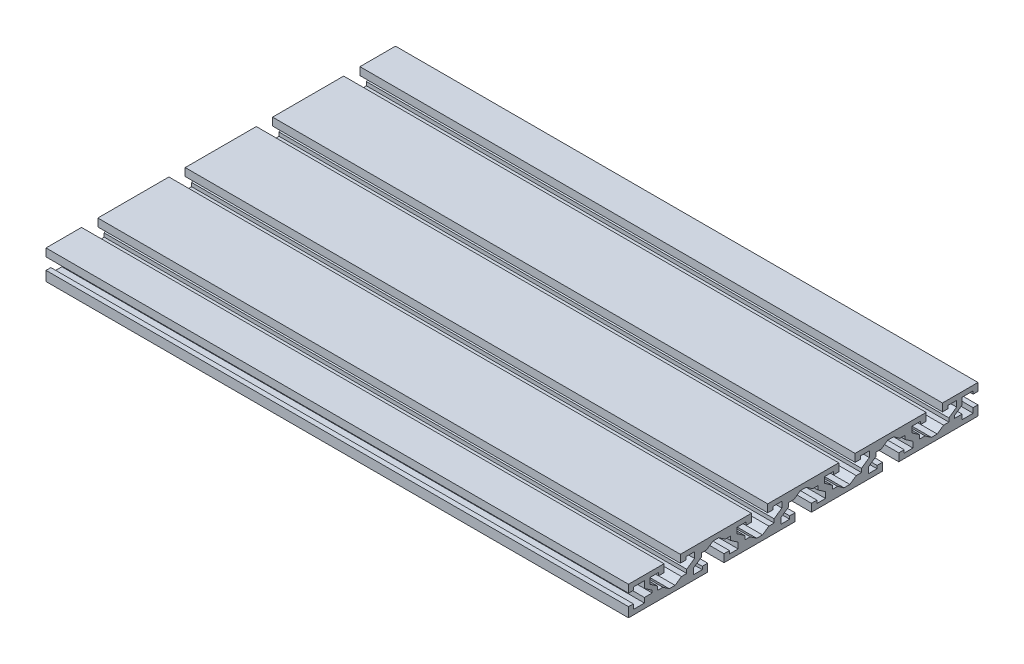
SolidWorks part; units mm, degrees
material "1060 Сплав"
ref_plane "Спереди" through (0, 0, 0) normal (0, 0, 1) x (1, 0, 0)
ref_plane "Сверху" through (0, 0, 0) normal (0, 1, 0) x (1, 0, 0)
ref_plane "Справа" through (0, 0, 0) normal (1, 0, 0) x (0, 0, -1)
other "Configuration Table"
sketch "Эскиз1" plane through (0, 0, 0) normal (0, 1, 0) x (1, 0, 0)
  line L1 (-150, -90) -> (150, -90)
  line L2 (-150, -90) -> (-150, 90)
  line L3 (-150, 90) -> (150, 90)
  line L4 (150, -90) -> (150, 90)
  line L5 (-150, -90) -> (150, 90) construction
  line L6 (-150, 90) -> (150, -90) construction
  point P0 (0, 0)
  dimension "D1" = 300
  dimension "D2" = 180
extrude "Бобышка-Вытянуть1" add sketch "Эскиз1" along normal blind 15
sketch "Эскиз3" plane through (0, 0, 0) normal (1, 0, 0) x (0, 0, -1)
  line L0 (0, -1000) -> (0, 49000) construction
  line L1 (4.2, 0) -> (4.2, 4)
  line L2 (-4.2, 0) -> (-4.2, 4)
  line L3 (-4.2, 4) -> (-7, 4)
  line L4 (-90, 0) -> (90, 0)
  line L5 (-90, 15) -> (-90, 0)
  line L6 (90, 15) -> (-90, 15)
  line L7 (90, 0) -> (90, 15)
  line L8 (-90, 0) -> (90, 0)
  line L9 (-90, 15) -> (-90, 0)
  line L10 (90, 15) -> (-90, 15)
  line L11 (90, 0) -> (90, 15)
  line L12 (-7, 4) -> (-7, 2.5)
  line L13 (-7, 2.5) -> (-11.5, 2.5)
  line L14 (-11.5, 2.5) -> (-11.5, 5.5)
  line L15 (-11.5, 5.5) -> (-7.5, 8.3)
  line L16 (-7.5, 8.3) -> (-7.5, 10.2)
  line L17 (-7.5, 10.2) -> (-4.7857, 10.2)
  line L18 (-4.7857, 10.2) -> (-1.5, 12.5)
  line L19 (-1.5, 12.5) -> (1.5, 12.5)
  line L20 (-7.5, 8.3) -> (-4.7857, 10.2) construction
  line L21 (4.7857, 10.2) -> (1.5, 12.5)
  line L22 (4.2, 4) -> (7, 4)
  line L23 (7.5, 10.2) -> (4.7857, 10.2)
  line L24 (7.5, 8.3) -> (7.5, 10.2)
  line L25 (11.5, 5.5) -> (7.5, 8.3)
  line L26 (11.5, 2.5) -> (11.5, 5.5)
  line L27 (7, 2.5) -> (11.5, 2.5)
  line L28 (7, 4) -> (7, 2.5)
  line L29 (49.2, 0) -> (49.2, 4)
  line L30 (40.8, 0) -> (40.8, 4)
  line L31 (40.8, 4) -> (38, 4)
  line L32 (38, 4) -> (38, 2.5)
  line L33 (38, 2.5) -> (33.5, 2.5)
  line L34 (33.5, 2.5) -> (33.5, 5.5)
  line L35 (33.5, 5.5) -> (37.5, 8.3)
  line L36 (37.5, 8.3) -> (37.5, 10.2)
  line L37 (37.5, 10.2) -> (40.2143, 10.2)
  line L38 (40.2143, 10.2) -> (43.5, 12.5)
  line L39 (43.5, 12.5) -> (46.5, 12.5)
  line L40 (49.7857, 10.2) -> (46.5, 12.5)
  line L41 (49.2, 4) -> (52, 4)
  line L42 (52.5, 10.2) -> (49.7857, 10.2)
  line L43 (52.5, 8.3) -> (52.5, 10.2)
  line L44 (56.5, 5.5) -> (52.5, 8.3)
  line L45 (56.5, 2.5) -> (56.5, 5.5)
  line L46 (52, 2.5) -> (56.5, 2.5)
  line L47 (52, 4) -> (52, 2.5)
  line L48 (37.5, 8.3) -> (40.2143, 10.2) construction
  line L49 (-40.8, 0) -> (-40.8, 4)
  line L50 (-49.2, 0) -> (-49.2, 4)
  line L51 (-49.2, 4) -> (-52, 4)
  line L52 (-52, 4) -> (-52, 2.5)
  line L53 (-52, 2.5) -> (-56.5, 2.5)
  line L54 (-56.5, 2.5) -> (-56.5, 5.5)
  line L55 (-56.5, 5.5) -> (-52.5, 8.3)
  line L56 (-52.5, 8.3) -> (-52.5, 10.2)
  line L57 (-52.5, 10.2) -> (-49.7857, 10.2)
  line L58 (-49.7857, 10.2) -> (-46.5, 12.5)
  line L59 (-46.5, 12.5) -> (-43.5, 12.5)
  line L60 (-40.2143, 10.2) -> (-43.5, 12.5)
  line L61 (-40.8, 4) -> (-38, 4)
  line L62 (-37.5, 10.2) -> (-40.2143, 10.2)
  line L63 (-37.5, 8.3) -> (-37.5, 10.2)
  line L64 (-33.5, 5.5) -> (-37.5, 8.3)
  line L65 (-33.5, 2.5) -> (-33.5, 5.5)
  line L66 (-38, 2.5) -> (-33.5, 2.5)
  line L67 (-38, 4) -> (-38, 2.5)
  line L68 (-52.5, 8.3) -> (-49.7857, 10.2) construction
  point P7 (0, 0)
  point P11 (4.2, 2)
  point P23 (0, 12.5)
  point P46 (45, 12.5)
  point P67 (-45, 12.5)
  dimension "D2" = 8.4
  dimension "D3" = 4
  dimension "D4" = 2.8
  dimension "D5" = 2.5
  dimension "D6" = 23
  dimension "D7" = 2.5
  dimension "D8" = 3
  dimension "D9" = 15
  dimension "D10" = 4.8
  dimension "D11" = 3
  dimension "D12" = 2
  dimension "D13" = 45
  dimension "D14" = 2
  dimension "D15" = 45
  dimension "D1" = 0
extrude "Вырез-Вытянуть1" cut sketch "Эскиз3" against normal through all both and the other way through all contours L61 L67 L66 L65 L64 L63 L62 L60 L59 L58 L57 L56 L55 L54 L53 L52 L51 L50 L8 L49 | L22 L28 L27 L26 L25 L24 L23 L21 L19 L18 L17 L16 L15 L14 L13 L12 L3 L2 L8 L1 | L41 L47 L46 L45 L44 L43 L42 L40 L39 L38 L37 L36 L35 L34 L33 L32 L31 L30 L8 L29
sketch "Эскиз4" plane through (0, 0, 0) normal (1, 0, 0) x (0, 0, -1)
  line L18 (-71.7, 11) -> (-71.7, 15)
  line L19 (-71.7, 15) -> (-63.3, 15) construction
  line L20 (0, -1000) -> (0, 49000) construction
  line L21 (-71.7, 11) -> (-74.5, 11)
  line L22 (-74.5, 11) -> (-74.5, 12.5)
  line L23 (-74.5, 12.5) -> (-79, 12.5)
  line L24 (-79, 12.5) -> (-79, 9.5)
  line L25 (-79, 9.5) -> (-75, 6.7)
  line L26 (-75, 6.7) -> (-75, 4.8)
  line L27 (-75, 4.8) -> (-72.2857, 4.8)
  line L28 (-72.2857, 4.8) -> (-69, 2.5)
  line L29 (-69, 2.5) -> (-66, 2.5)
  line L30 (-66, 2.5) -> (-62.7143, 4.8)
  line L31 (-62.7143, 4.8) -> (-60, 4.8)
  line L32 (-60, 4.8) -> (-60, 6.7)
  line L33 (-60, 6.7) -> (-56, 9.5)
  line L34 (-56, 9.5) -> (-56, 12.5)
  line L35 (-56, 12.5) -> (-60.5, 12.5)
  line L36 (-60.5, 12.5) -> (-60.5, 11)
  line L37 (-60.5, 11) -> (-63.3, 11)
  line L38 (-63.3, 11) -> (-63.3, 15)
  line L39 (-67.5, 2.5) -> (-67.5, 15) construction
  line L40 (-26.7, 11) -> (-29.5, 11)
  line L41 (-29.5, 11) -> (-29.5, 12.5)
  line L42 (-29.5, 12.5) -> (-34, 12.5)
  line L43 (-34, 12.5) -> (-34, 9.5)
  line L44 (-34, 9.5) -> (-30, 6.7)
  line L45 (-30, 6.7) -> (-30, 4.8)
  line L46 (-30, 4.8) -> (-27.2857, 4.8)
  line L47 (-27.2857, 4.8) -> (-24, 2.5)
  line L48 (-24, 2.5) -> (-21, 2.5)
  line L49 (-21, 2.5) -> (-17.7143, 4.8)
  line L50 (-17.7143, 4.8) -> (-15, 4.8)
  line L51 (-15, 4.8) -> (-15, 6.7)
  line L52 (-15, 6.7) -> (-11, 9.5)
  line L53 (-11, 9.5) -> (-11, 12.5)
  line L54 (-11, 12.5) -> (-15.5, 12.5)
  line L55 (-15.5, 12.5) -> (-15.5, 11)
  line L56 (-15.5, 11) -> (-18.3, 11)
  line L57 (-26.7, 11) -> (-26.7, 15)
  line L58 (-18.3, 11) -> (-18.3, 15)
  line L59 (18.3, 11) -> (15.5, 11)
  line L60 (15.5, 11) -> (15.5, 12.5)
  line L61 (15.5, 12.5) -> (11, 12.5)
  line L62 (11, 12.5) -> (11, 9.5)
  line L63 (11, 9.5) -> (15, 6.7)
  line L64 (-40.8, 0) -> (-4.2, 0)
  line L65 (-40.8, 4) -> (-40.8, 0)
  line L66 (-38, 4) -> (-40.8, 4)
  line L67 (-38, 2.5) -> (-38, 4)
  line L68 (-33.5, 2.5) -> (-38, 2.5)
  line L69 (-33.5, 5.5) -> (-33.5, 2.5)
  line L70 (-37.5, 8.3) -> (-33.5, 5.5)
  line L71 (-37.5, 10.2) -> (-37.5, 8.3)
  line L72 (-40.2143, 10.2) -> (-37.5, 10.2)
  line L73 (-43.5, 12.5) -> (-40.2143, 10.2)
  line L74 (-46.5, 12.5) -> (-43.5, 12.5)
  line L75 (-49.7857, 10.2) -> (-46.5, 12.5)
  line L76 (-52.5, 10.2) -> (-49.7857, 10.2)
  line L77 (-52.5, 8.3) -> (-52.5, 10.2)
  line L78 (-56.5, 5.5) -> (-52.5, 8.3)
  line L79 (-56.5, 2.5) -> (-56.5, 5.5)
  line L80 (-52, 2.5) -> (-56.5, 2.5)
  line L81 (-52, 4) -> (-52, 2.5)
  line L82 (-49.2, 4) -> (-52, 4)
  line L83 (-49.2, 0) -> (-49.2, 4)
  line L84 (-90, 0) -> (-49.2, 0)
  line L85 (-90, 15) -> (-90, 0)
  line L86 (90, 15) -> (-90, 15)
  line L87 (90, 0) -> (90, 15)
  line L88 (49.2, 0) -> (90, 0)
  line L89 (49.2, 4) -> (49.2, 0)
  line L90 (52, 4) -> (49.2, 4)
  line L91 (52, 2.5) -> (52, 4)
  line L92 (56.5, 2.5) -> (52, 2.5)
  line L93 (56.5, 5.5) -> (56.5, 2.5)
  line L94 (52.5, 8.3) -> (56.5, 5.5)
  line L95 (52.5, 10.2) -> (52.5, 8.3)
  line L96 (49.7857, 10.2) -> (52.5, 10.2)
  line L97 (46.5, 12.5) -> (49.7857, 10.2)
  line L98 (43.5, 12.5) -> (46.5, 12.5)
  line L99 (40.2143, 10.2) -> (43.5, 12.5)
  line L100 (37.5, 10.2) -> (40.2143, 10.2)
  line L101 (37.5, 8.3) -> (37.5, 10.2)
  line L102 (33.5, 5.5) -> (37.5, 8.3)
  line L103 (33.5, 2.5) -> (33.5, 5.5)
  line L104 (38, 2.5) -> (33.5, 2.5)
  line L105 (38, 4) -> (38, 2.5)
  line L106 (40.8, 4) -> (38, 4)
  line L107 (40.8, 0) -> (40.8, 4)
  line L108 (4.2, 0) -> (40.8, 0)
  line L109 (4.2, 4) -> (4.2, 0)
  line L110 (7, 4) -> (4.2, 4)
  line L111 (7, 2.5) -> (7, 4)
  line L112 (11.5, 2.5) -> (7, 2.5)
  line L113 (11.5, 5.5) -> (11.5, 2.5)
  line L114 (7.5, 8.3) -> (11.5, 5.5)
  line L115 (7.5, 10.2) -> (7.5, 8.3)
  line L116 (4.7857, 10.2) -> (7.5, 10.2)
  line L117 (1.5, 12.5) -> (4.7857, 10.2)
  line L118 (-1.5, 12.5) -> (1.5, 12.5)
  line L119 (-4.7857, 10.2) -> (-1.5, 12.5)
  line L120 (-7.5, 10.2) -> (-4.7857, 10.2)
  line L121 (-7.5, 8.3) -> (-7.5, 10.2)
  line L122 (-11.5, 5.5) -> (-7.5, 8.3)
  line L123 (-11.5, 2.5) -> (-11.5, 5.5)
  line L124 (-7, 2.5) -> (-11.5, 2.5)
  line L125 (-7, 4) -> (-7, 2.5)
  line L126 (-4.2, 4) -> (-7, 4)
  line L127 (-4.2, 0) -> (-4.2, 4)
  line L128 (-40.8, 0) -> (-4.2, 0)
  line L129 (-40.8, 4) -> (-40.8, 0)
  line L130 (-38, 4) -> (-40.8, 4)
  line L131 (-38, 2.5) -> (-38, 4)
  line L132 (-33.5, 2.5) -> (-38, 2.5)
  line L133 (-33.5, 5.5) -> (-33.5, 2.5)
  line L134 (-37.5, 8.3) -> (-33.5, 5.5)
  line L135 (-37.5, 10.2) -> (-37.5, 8.3)
  line L136 (-40.2143, 10.2) -> (-37.5, 10.2)
  line L137 (-43.5, 12.5) -> (-40.2143, 10.2)
  line L138 (-46.5, 12.5) -> (-43.5, 12.5)
  line L139 (-49.7857, 10.2) -> (-46.5, 12.5)
  line L140 (-52.5, 10.2) -> (-49.7857, 10.2)
  line L141 (-52.5, 8.3) -> (-52.5, 10.2)
  line L142 (-56.5, 5.5) -> (-52.5, 8.3)
  line L143 (-56.5, 2.5) -> (-56.5, 5.5)
  line L144 (-52, 2.5) -> (-56.5, 2.5)
  line L145 (-52, 4) -> (-52, 2.5)
  line L146 (-49.2, 4) -> (-52, 4)
  line L147 (-49.2, 0) -> (-49.2, 4)
  line L148 (-90, 0) -> (-49.2, 0)
  line L149 (-90, 15) -> (-90, 0)
  line L150 (90, 15) -> (-90, 15)
  line L151 (90, 0) -> (90, 15)
  line L152 (49.2, 0) -> (90, 0)
  line L153 (49.2, 4) -> (49.2, 0)
  line L154 (52, 4) -> (49.2, 4)
  line L155 (52, 2.5) -> (52, 4)
  line L156 (56.5, 2.5) -> (52, 2.5)
  line L157 (56.5, 5.5) -> (56.5, 2.5)
  line L158 (52.5, 8.3) -> (56.5, 5.5)
  line L159 (52.5, 10.2) -> (52.5, 8.3)
  line L160 (49.7857, 10.2) -> (52.5, 10.2)
  line L161 (46.5, 12.5) -> (49.7857, 10.2)
  line L162 (43.5, 12.5) -> (46.5, 12.5)
  line L163 (40.2143, 10.2) -> (43.5, 12.5)
  line L164 (37.5, 10.2) -> (40.2143, 10.2)
  line L165 (37.5, 8.3) -> (37.5, 10.2)
  line L166 (33.5, 5.5) -> (37.5, 8.3)
  line L167 (33.5, 2.5) -> (33.5, 5.5)
  line L168 (38, 2.5) -> (33.5, 2.5)
  line L169 (38, 4) -> (38, 2.5)
  line L170 (40.8, 4) -> (38, 4)
  line L171 (40.8, 0) -> (40.8, 4)
  line L172 (4.2, 0) -> (40.8, 0)
  line L173 (4.2, 4) -> (4.2, 0)
  line L174 (7, 4) -> (4.2, 4)
  line L175 (7, 2.5) -> (7, 4)
  line L176 (11.5, 2.5) -> (7, 2.5)
  line L177 (11.5, 5.5) -> (11.5, 2.5)
  line L178 (7.5, 8.3) -> (11.5, 5.5)
  line L179 (7.5, 10.2) -> (7.5, 8.3)
  line L180 (4.7857, 10.2) -> (7.5, 10.2)
  line L181 (1.5, 12.5) -> (4.7857, 10.2)
  line L182 (-1.5, 12.5) -> (1.5, 12.5)
  line L183 (-4.7857, 10.2) -> (-1.5, 12.5)
  line L184 (-7.5, 10.2) -> (-4.7857, 10.2)
  line L185 (-7.5, 8.3) -> (-7.5, 10.2)
  line L186 (-11.5, 5.5) -> (-7.5, 8.3)
  line L187 (-11.5, 2.5) -> (-11.5, 5.5)
  line L188 (-7, 2.5) -> (-11.5, 2.5)
  line L189 (-7, 4) -> (-7, 2.5)
  line L190 (-4.2, 4) -> (-7, 4)
  line L191 (-4.2, 0) -> (-4.2, 4)
  line L192 (15, 6.7) -> (15, 4.8)
  line L193 (15, 4.8) -> (17.7143, 4.8)
  line L194 (17.7143, 4.8) -> (21, 2.5)
  line L195 (21, 2.5) -> (24, 2.5)
  line L196 (24, 2.5) -> (27.2857, 4.8)
  line L197 (27.2857, 4.8) -> (30, 4.8)
  line L198 (30, 4.8) -> (30, 6.7)
  line L199 (30, 6.7) -> (34, 9.5)
  line L200 (34, 9.5) -> (34, 12.5)
  line L201 (34, 12.5) -> (29.5, 12.5)
  line L202 (29.5, 12.5) -> (29.5, 11)
  line L203 (29.5, 11) -> (26.7, 11)
  line L204 (18.3, 11) -> (18.3, 15)
  line L205 (26.7, 11) -> (26.7, 15)
  line L206 (63.3, 11) -> (60.5, 11)
  line L207 (60.5, 11) -> (60.5, 12.5)
  line L208 (60.5, 12.5) -> (56, 12.5)
  line L209 (56, 12.5) -> (56, 9.5)
  line L210 (56, 9.5) -> (60, 6.7)
  line L211 (60, 6.7) -> (60, 4.8)
  line L212 (60, 4.8) -> (62.7143, 4.8)
  line L213 (62.7143, 4.8) -> (66, 2.5)
  line L214 (66, 2.5) -> (69, 2.5)
  line L215 (69, 2.5) -> (72.2857, 4.8)
  line L216 (72.2857, 4.8) -> (75, 4.8)
  line L217 (75, 4.8) -> (75, 6.7)
  line L218 (75, 6.7) -> (79, 9.5)
  line L219 (79, 9.5) -> (79, 12.5)
  line L220 (79, 12.5) -> (74.5, 12.5)
  line L221 (74.5, 12.5) -> (74.5, 11)
  line L222 (74.5, 11) -> (71.7, 11)
  line L223 (63.3, 11) -> (63.3, 15)
  line L224 (71.7, 11) -> (71.7, 15)
  line L225 (-71.7, 11) -> (-26.7, 11) construction
  dimension "D2" = 8.4
  dimension "D3" = 23
  dimension "D4" = 2.3
  dimension "D5" = 12.5
  dimension "D6" = 4
  dimension "D7" = 3
  dimension "D8" = 14
  dimension "D9" = 3
  dimension "D10" = 1.5
  dimension "D11" = 15
  dimension "D12" = 67.5
  dimension "D14" = 45
  dimension "D1" = 0
  dimension "D13" = 4
extrude "Вырез-Вытянуть2" cut sketch "Эскиз4" against normal through all both and the other way through all contours L38 L150 L18 L21 L22 L23 L24 L25 L26 L27 L28 L29 L30 L31 L32 L33 L34 L35 L36 L37 | L58 L150 L57 L40 L41 L42 L43 L44 L45 L46 L47 L48 L49 L50 L51 L52 L53 L54 L55 L56 | L203 L205 L150 L204 L59 L60 L61 L62 L63 L192 L193 L194 L195 L196 L197 L198 L199 L200 L201 L202 | L222 L224 L150 L223 L206 L207 L208 L209 L210 L211 L212 L213 L214 L215 L216 L217 L218 L219 L220 L221
sketch "Эскиз5" plane through (0, 0, 0) normal (1, 0, 0) x (0, 0, -1)
  line L0 (0, -1000) -> (0, 49000) construction
  line L1 (90, 11) -> (87.5, 11)
  line L2 (87.5, 11) -> (87.5, 12.5)
  line L3 (87.5, 12.5) -> (81.8, 12.5)
  line L4 (81.8, 12.5) -> (81.8, 9.0187)
  line L5 (81.8, 9.0187) -> (77.8, 6.2187)
  line L6 (77.8, 6.2187) -> (77.8, 5)
  line L7 (77.8, 5) -> (81.8, 5)
  line L8 (81.8, 5) -> (81.8, 2.5)
  line L9 (81.8, 2.5) -> (87.5, 2.5)
  line L10 (87.5, 2.5) -> (87.5, 5)
  line L11 (87.5, 5) -> (90, 5)
  line L12 (-87.5, 11) -> (-87.5, 12.5)
  line L13 (-87.5, 12.5) -> (-81.8, 12.5)
  line L14 (-81.8, 12.5) -> (-81.8, 9.0187)
  line L15 (-87.5, 5) -> (-90, 5)
  line L16 (-87.5, 2.5) -> (-87.5, 5)
  line L17 (-81.8, 2.5) -> (-87.5, 2.5)
  line L18 (-81.8, 5) -> (-81.8, 2.5)
  line L19 (-77.8, 5) -> (-81.8, 5)
  line L20 (-77.8, 6.2187) -> (-77.8, 5)
  line L21 (-81.8, 9.0187) -> (-77.8, 6.2187)
  line L22 (-90, 11) -> (-87.5, 11)
  line L144 (-26.7, 15) -> (-63.3, 15)
  line L145 (-63.3, 15) -> (-63.3, 11)
  line L146 (-63.3, 11) -> (-60.5, 11)
  line L147 (-60.5, 11) -> (-60.5, 12.5)
  line L148 (-60.5, 12.5) -> (-56, 12.5)
  line L149 (-56, 12.5) -> (-56, 9.5)
  line L150 (-56, 9.5) -> (-60, 6.7)
  line L151 (-60, 6.7) -> (-60, 4.8)
  line L152 (-60, 4.8) -> (-62.7143, 4.8)
  line L153 (-62.7143, 4.8) -> (-66, 2.5)
  line L154 (-66, 2.5) -> (-69, 2.5)
  line L155 (-69, 2.5) -> (-72.2857, 4.8)
  line L156 (-72.2857, 4.8) -> (-75, 4.8)
  line L157 (-75, 4.8) -> (-75, 6.7)
  line L158 (-75, 6.7) -> (-79, 9.5)
  line L159 (-79, 9.5) -> (-79, 12.5)
  line L160 (-79, 12.5) -> (-74.5, 12.5)
  line L161 (-74.5, 12.5) -> (-74.5, 11)
  line L162 (-74.5, 11) -> (-71.7, 11)
  line L163 (-71.7, 11) -> (-71.7, 15)
  line L164 (-71.7, 15) -> (-90, 15)
  line L165 (-90, 15) -> (-90, 0)
  line L166 (-90, 0) -> (-49.2, 0)
  line L167 (-49.2, 0) -> (-49.2, 4)
  line L168 (-49.2, 4) -> (-52, 4)
  line L169 (-52, 4) -> (-52, 2.5)
  line L170 (-52, 2.5) -> (-56.5, 2.5)
  line L171 (-56.5, 2.5) -> (-56.5, 5.5)
  line L172 (-56.5, 5.5) -> (-52.5, 8.3)
  line L173 (-52.5, 8.3) -> (-52.5, 10.2)
  line L174 (-52.5, 10.2) -> (-49.7857, 10.2)
  line L175 (-49.7857, 10.2) -> (-46.5, 12.5)
  line L176 (-46.5, 12.5) -> (-43.5, 12.5)
  line L177 (-43.5, 12.5) -> (-40.2143, 10.2)
  line L178 (-40.2143, 10.2) -> (-37.5, 10.2)
  line L179 (-37.5, 10.2) -> (-37.5, 8.3)
  line L180 (-37.5, 8.3) -> (-33.5, 5.5)
  line L181 (-33.5, 5.5) -> (-33.5, 2.5)
  line L182 (-33.5, 2.5) -> (-38, 2.5)
  line L183 (-38, 2.5) -> (-38, 4)
  line L184 (-38, 4) -> (-40.8, 4)
  line L185 (-40.8, 4) -> (-40.8, 0)
  line L186 (-40.8, 0) -> (-4.2, 0)
  line L187 (-4.2, 0) -> (-4.2, 4)
  line L188 (-4.2, 4) -> (-7, 4)
  line L189 (-7, 4) -> (-7, 2.5)
  line L190 (-7, 2.5) -> (-11.5, 2.5)
  line L191 (-11.5, 2.5) -> (-11.5, 5.5)
  line L192 (-11.5, 5.5) -> (-7.5, 8.3)
  line L193 (-7.5, 8.3) -> (-7.5, 10.2)
  line L194 (-7.5, 10.2) -> (-4.7857, 10.2)
  line L195 (-4.7857, 10.2) -> (-1.5, 12.5)
  line L196 (-1.5, 12.5) -> (1.5, 12.5)
  line L197 (1.5, 12.5) -> (4.7857, 10.2)
  line L198 (4.7857, 10.2) -> (7.5, 10.2)
  line L199 (7.5, 10.2) -> (7.5, 8.3)
  line L200 (7.5, 8.3) -> (11.5, 5.5)
  line L201 (11.5, 5.5) -> (11.5, 2.5)
  line L202 (11.5, 2.5) -> (7, 2.5)
  line L203 (7, 2.5) -> (7, 4)
  line L204 (7, 4) -> (4.2, 4)
  line L205 (4.2, 4) -> (4.2, 0)
  line L206 (4.2, 0) -> (40.8, 0)
  line L207 (40.8, 0) -> (40.8, 4)
  line L208 (40.8, 4) -> (38, 4)
  line L209 (38, 4) -> (38, 2.5)
  line L210 (38, 2.5) -> (33.5, 2.5)
  line L211 (33.5, 2.5) -> (33.5, 5.5)
  line L212 (33.5, 5.5) -> (37.5, 8.3)
  line L213 (37.5, 8.3) -> (37.5, 10.2)
  line L214 (37.5, 10.2) -> (40.2143, 10.2)
  line L215 (40.2143, 10.2) -> (43.5, 12.5)
  line L216 (43.5, 12.5) -> (46.5, 12.5)
  line L217 (46.5, 12.5) -> (49.7857, 10.2)
  line L218 (49.7857, 10.2) -> (52.5, 10.2)
  line L219 (52.5, 10.2) -> (52.5, 8.3)
  line L220 (52.5, 8.3) -> (56.5, 5.5)
  line L221 (56.5, 5.5) -> (56.5, 2.5)
  line L222 (56.5, 2.5) -> (52, 2.5)
  line L223 (52, 2.5) -> (52, 4)
  line L224 (52, 4) -> (49.2, 4)
  line L225 (49.2, 4) -> (49.2, 0)
  line L226 (49.2, 0) -> (90, 0)
  line L227 (90, 0) -> (90, 15)
  line L228 (90, 15) -> (71.7, 15)
  line L229 (71.7, 15) -> (71.7, 11)
  line L230 (71.7, 11) -> (74.5, 11)
  line L231 (74.5, 11) -> (74.5, 12.5)
  line L232 (74.5, 12.5) -> (79, 12.5)
  line L233 (79, 12.5) -> (79, 9.5)
  line L234 (79, 9.5) -> (75, 6.7)
  line L235 (75, 6.7) -> (75, 4.8)
  line L236 (75, 4.8) -> (72.2857, 4.8)
  line L237 (72.2857, 4.8) -> (69, 2.5)
  line L238 (69, 2.5) -> (66, 2.5)
  line L239 (66, 2.5) -> (62.7143, 4.8)
  line L240 (62.7143, 4.8) -> (60, 4.8)
  line L241 (60, 4.8) -> (60, 6.7)
  line L242 (60, 6.7) -> (56, 9.5)
  line L243 (56, 9.5) -> (56, 12.5)
  line L244 (56, 12.5) -> (60.5, 12.5)
  line L245 (60.5, 12.5) -> (60.5, 11)
  line L246 (60.5, 11) -> (63.3, 11)
  line L247 (63.3, 11) -> (63.3, 15)
  line L248 (63.3, 15) -> (26.7, 15)
  line L249 (26.7, 15) -> (26.7, 11)
  line L250 (26.7, 11) -> (29.5, 11)
  line L251 (29.5, 11) -> (29.5, 12.5)
  line L252 (29.5, 12.5) -> (34, 12.5)
  line L253 (34, 12.5) -> (34, 9.5)
  line L254 (34, 9.5) -> (30, 6.7)
  line L255 (30, 6.7) -> (30, 4.8)
  line L256 (30, 4.8) -> (27.2857, 4.8)
  line L257 (27.2857, 4.8) -> (24, 2.5)
  line L258 (24, 2.5) -> (21, 2.5)
  line L259 (21, 2.5) -> (17.7143, 4.8)
  line L260 (17.7143, 4.8) -> (15, 4.8)
  line L261 (15, 4.8) -> (15, 6.7)
  line L262 (15, 6.7) -> (11, 9.5)
  line L263 (11, 9.5) -> (11, 12.5)
  line L264 (11, 12.5) -> (15.5, 12.5)
  line L265 (15.5, 12.5) -> (15.5, 11)
  line L266 (15.5, 11) -> (18.3, 11)
  line L267 (18.3, 11) -> (18.3, 15)
  line L268 (18.3, 15) -> (-18.3, 15)
  line L269 (-18.3, 15) -> (-18.3, 11)
  line L270 (-18.3, 11) -> (-15.5, 11)
  line L271 (-15.5, 11) -> (-15.5, 12.5)
  line L272 (-15.5, 12.5) -> (-11, 12.5)
  line L273 (-11, 12.5) -> (-11, 9.5)
  line L274 (-11, 9.5) -> (-15, 6.7)
  line L275 (-15, 6.7) -> (-15, 4.8)
  line L276 (-15, 4.8) -> (-17.7143, 4.8)
  line L277 (-17.7143, 4.8) -> (-21, 2.5)
  line L278 (-21, 2.5) -> (-24, 2.5)
  line L279 (-24, 2.5) -> (-27.2857, 4.8)
  line L280 (-27.2857, 4.8) -> (-30, 4.8)
  line L281 (-30, 4.8) -> (-30, 6.7)
  line L282 (-30, 6.7) -> (-34, 9.5)
  line L283 (-34, 9.5) -> (-34, 12.5)
  line L284 (-34, 12.5) -> (-29.5, 12.5)
  line L285 (-29.5, 12.5) -> (-29.5, 11)
  line L286 (-29.5, 11) -> (-26.7, 11)
  line L287 (-26.7, 11) -> (-26.7, 15)
  line L288 (-26.7, 15) -> (-63.3, 15)
  line L289 (-63.3, 15) -> (-63.3, 11)
  line L290 (-63.3, 11) -> (-60.5, 11)
  line L291 (-60.5, 11) -> (-60.5, 12.5)
  line L292 (-60.5, 12.5) -> (-56, 12.5)
  line L293 (-56, 12.5) -> (-56, 9.5)
  line L294 (-56, 9.5) -> (-60, 6.7)
  line L295 (-60, 6.7) -> (-60, 4.8)
  line L296 (-60, 4.8) -> (-62.7143, 4.8)
  line L297 (-62.7143, 4.8) -> (-66, 2.5)
  line L298 (-66, 2.5) -> (-69, 2.5)
  line L299 (-69, 2.5) -> (-72.2857, 4.8)
  line L300 (-72.2857, 4.8) -> (-75, 4.8)
  line L301 (-75, 4.8) -> (-75, 6.7)
  line L302 (-75, 6.7) -> (-79, 9.5)
  line L303 (-79, 9.5) -> (-79, 12.5)
  line L304 (-79, 12.5) -> (-74.5, 12.5)
  line L305 (-74.5, 12.5) -> (-74.5, 11)
  line L306 (-74.5, 11) -> (-71.7, 11)
  line L307 (-71.7, 11) -> (-71.7, 15)
  line L308 (-71.7, 15) -> (-90, 15)
  line L309 (-90, 15) -> (-90, 0)
  line L310 (-90, 0) -> (-49.2, 0)
  line L311 (-49.2, 0) -> (-49.2, 4)
  line L312 (-49.2, 4) -> (-52, 4)
  line L313 (-52, 4) -> (-52, 2.5)
  line L314 (-52, 2.5) -> (-56.5, 2.5)
  line L315 (-56.5, 2.5) -> (-56.5, 5.5)
  line L316 (-56.5, 5.5) -> (-52.5, 8.3)
  line L317 (-52.5, 8.3) -> (-52.5, 10.2)
  line L318 (-52.5, 10.2) -> (-49.7857, 10.2)
  line L319 (-49.7857, 10.2) -> (-46.5, 12.5)
  line L320 (-46.5, 12.5) -> (-43.5, 12.5)
  line L321 (-43.5, 12.5) -> (-40.2143, 10.2)
  line L322 (-40.2143, 10.2) -> (-37.5, 10.2)
  line L323 (-37.5, 10.2) -> (-37.5, 8.3)
  line L324 (-37.5, 8.3) -> (-33.5, 5.5)
  line L325 (-33.5, 5.5) -> (-33.5, 2.5)
  line L326 (-33.5, 2.5) -> (-38, 2.5)
  line L327 (-38, 2.5) -> (-38, 4)
  line L328 (-38, 4) -> (-40.8, 4)
  line L329 (-40.8, 4) -> (-40.8, 0)
  line L330 (-40.8, 0) -> (-4.2, 0)
  line L331 (-4.2, 0) -> (-4.2, 4)
  line L332 (-4.2, 4) -> (-7, 4)
  line L333 (-7, 4) -> (-7, 2.5)
  line L334 (-7, 2.5) -> (-11.5, 2.5)
  line L335 (-11.5, 2.5) -> (-11.5, 5.5)
  line L336 (-11.5, 5.5) -> (-7.5, 8.3)
  line L337 (-7.5, 8.3) -> (-7.5, 10.2)
  line L338 (-7.5, 10.2) -> (-4.7857, 10.2)
  line L339 (-4.7857, 10.2) -> (-1.5, 12.5)
  line L340 (-1.5, 12.5) -> (1.5, 12.5)
  line L341 (1.5, 12.5) -> (4.7857, 10.2)
  line L342 (4.7857, 10.2) -> (7.5, 10.2)
  line L343 (7.5, 10.2) -> (7.5, 8.3)
  line L344 (7.5, 8.3) -> (11.5, 5.5)
  line L345 (11.5, 5.5) -> (11.5, 2.5)
  line L346 (11.5, 2.5) -> (7, 2.5)
  line L347 (7, 2.5) -> (7, 4)
  line L348 (7, 4) -> (4.2, 4)
  line L349 (4.2, 4) -> (4.2, 0)
  line L350 (4.2, 0) -> (40.8, 0)
  line L351 (40.8, 0) -> (40.8, 4)
  line L352 (40.8, 4) -> (38, 4)
  line L353 (38, 4) -> (38, 2.5)
  line L354 (38, 2.5) -> (33.5, 2.5)
  line L355 (33.5, 2.5) -> (33.5, 5.5)
  line L356 (33.5, 5.5) -> (37.5, 8.3)
  line L357 (37.5, 8.3) -> (37.5, 10.2)
  line L358 (37.5, 10.2) -> (40.2143, 10.2)
  line L359 (40.2143, 10.2) -> (43.5, 12.5)
  line L360 (43.5, 12.5) -> (46.5, 12.5)
  line L361 (46.5, 12.5) -> (49.7857, 10.2)
  line L362 (49.7857, 10.2) -> (52.5, 10.2)
  line L363 (52.5, 10.2) -> (52.5, 8.3)
  line L364 (52.5, 8.3) -> (56.5, 5.5)
  line L365 (56.5, 5.5) -> (56.5, 2.5)
  line L366 (56.5, 2.5) -> (52, 2.5)
  line L367 (52, 2.5) -> (52, 4)
  line L368 (52, 4) -> (49.2, 4)
  line L369 (49.2, 4) -> (49.2, 0)
  line L370 (49.2, 0) -> (90, 0)
  line L371 (90, 0) -> (90, 15)
  line L372 (90, 15) -> (71.7, 15)
  line L373 (71.7, 15) -> (71.7, 11)
  line L374 (71.7, 11) -> (74.5, 11)
  line L375 (74.5, 11) -> (74.5, 12.5)
  line L376 (74.5, 12.5) -> (79, 12.5)
  line L377 (79, 12.5) -> (79, 9.5)
  line L378 (79, 9.5) -> (75, 6.7)
  line L379 (75, 6.7) -> (75, 4.8)
  line L380 (75, 4.8) -> (72.2857, 4.8)
  line L381 (72.2857, 4.8) -> (69, 2.5)
  line L382 (69, 2.5) -> (66, 2.5)
  line L383 (66, 2.5) -> (62.7143, 4.8)
  line L384 (62.7143, 4.8) -> (60, 4.8)
  line L385 (60, 4.8) -> (60, 6.7)
  line L386 (60, 6.7) -> (56, 9.5)
  line L387 (56, 9.5) -> (56, 12.5)
  line L388 (56, 12.5) -> (60.5, 12.5)
  line L389 (60.5, 12.5) -> (60.5, 11)
  line L390 (60.5, 11) -> (63.3, 11)
  line L391 (63.3, 11) -> (63.3, 15)
  line L392 (63.3, 15) -> (26.7, 15)
  line L393 (26.7, 15) -> (26.7, 11)
  line L394 (26.7, 11) -> (29.5, 11)
  line L395 (29.5, 11) -> (29.5, 12.5)
  line L396 (29.5, 12.5) -> (34, 12.5)
  line L397 (34, 12.5) -> (34, 9.5)
  line L398 (34, 9.5) -> (30, 6.7)
  line L399 (30, 6.7) -> (30, 4.8)
  line L400 (30, 4.8) -> (27.2857, 4.8)
  line L401 (27.2857, 4.8) -> (24, 2.5)
  line L402 (24, 2.5) -> (21, 2.5)
  line L403 (21, 2.5) -> (17.7143, 4.8)
  line L404 (17.7143, 4.8) -> (15, 4.8)
  line L405 (15, 4.8) -> (15, 6.7)
  line L406 (15, 6.7) -> (11, 9.5)
  line L407 (11, 9.5) -> (11, 12.5)
  line L408 (11, 12.5) -> (15.5, 12.5)
  line L409 (15.5, 12.5) -> (15.5, 11)
  line L410 (15.5, 11) -> (18.3, 11)
  line L411 (18.3, 11) -> (18.3, 15)
  line L412 (18.3, 15) -> (-18.3, 15)
  line L413 (-18.3, 15) -> (-18.3, 11)
  line L414 (-18.3, 11) -> (-15.5, 11)
  line L415 (-15.5, 11) -> (-15.5, 12.5)
  line L416 (-15.5, 12.5) -> (-11, 12.5)
  line L417 (-11, 12.5) -> (-11, 9.5)
  line L418 (-11, 9.5) -> (-15, 6.7)
  line L419 (-15, 6.7) -> (-15, 4.8)
  line L420 (-15, 4.8) -> (-17.7143, 4.8)
  line L421 (-17.7143, 4.8) -> (-21, 2.5)
  line L422 (-21, 2.5) -> (-24, 2.5)
  line L423 (-24, 2.5) -> (-27.2857, 4.8)
  line L424 (-27.2857, 4.8) -> (-30, 4.8)
  line L425 (-30, 4.8) -> (-30, 6.7)
  line L426 (-30, 6.7) -> (-34, 9.5)
  line L427 (-34, 9.5) -> (-34, 12.5)
  line L428 (-34, 12.5) -> (-29.5, 12.5)
  line L429 (-29.5, 12.5) -> (-29.5, 11)
  line L430 (-29.5, 11) -> (-26.7, 11)
  line L431 (-26.7, 11) -> (-26.7, 15)
  point P30 (77.8, 5.6093)
  dimension "D2" = 2.5
  dimension "D3" = 5
  dimension "D4" = 2.8
  dimension "D5" = 2.8
  dimension "D6" = 2
  dimension "D1" = 0
extrude "Вырез-Вытянуть3" cut sketch "Эскиз5" against normal through all both and the other way through all contours L22 L309 L15 L16 L17 L18 L19 L20 L21 L14 L13 L12 | L11 L371 L1 L2 L3 L4 L5 L6 L7 L8 L9 L10
